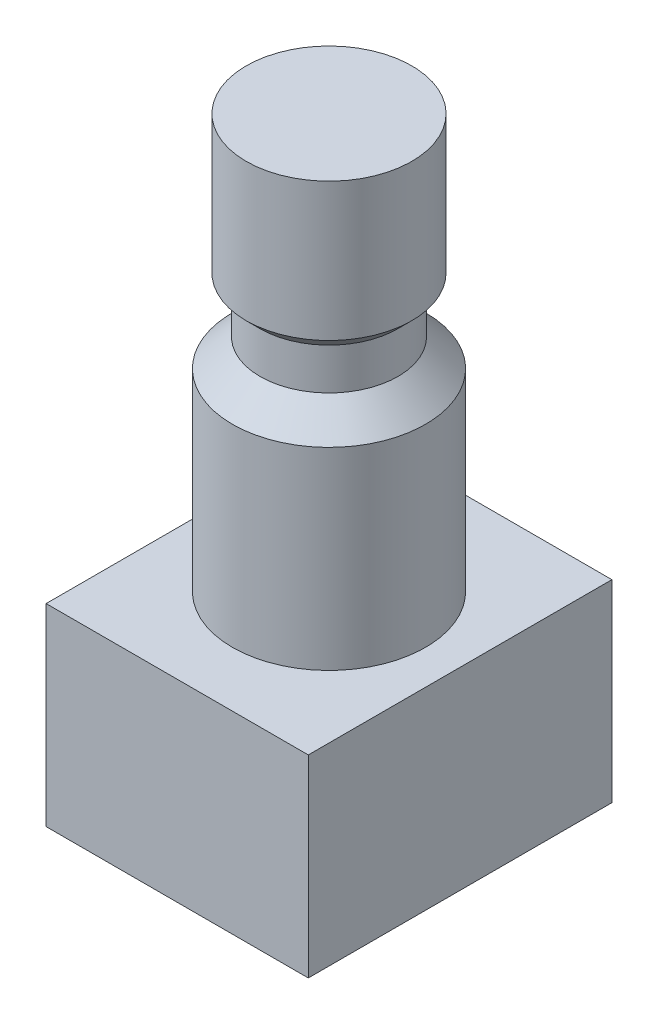
SolidWorks part; units mm, degrees
ref_plane "Plan de face" through (0, 0, 0) normal (0, 0, 1) x (1, 0, 0)
ref_plane "Plan de dessus" through (0, 0, 0) normal (0, 1, 0) x (1, 0, 0)
ref_plane "Plan de droite" through (0, 0, 0) normal (1, 0, 0) x (0, 0, -1)
sketch "Esquisse1" plane through (0, 0, 0) normal (0, 1, 0) x (1, 0, 0)
  line L0 (-4.75, 5.5) -> (4.75, -5.5) construction
  line L1 (-4.75, -5.5) -> (4.75, -5.5)
  line L2 (-4.75, -5.5) -> (-4.75, 5.5)
  line L3 (-4.75, 5.5) -> (4.75, 5.5)
  line L4 (4.75, -5.5) -> (4.75, 5.5)
  point P5 (0, 0)
  dimension "D1" = 11
  dimension "D2" = 9.5
extrude "Boss.-Extru.1" add sketch "Esquisse1" against normal blind 7
sketch "Esquisse3" plane through (0, 0, 0) normal (0, 0, 1) x (1, 0, 0)
  line L0 (0, 0) -> (0, 15)
  line L1 (0, 15) -> (3, 15)
  line L2 (3, 15) -> (3, 10)
  line L3 (3, 10) -> (2.5, 9.5)
  line L4 (2.5, 9.5) -> (2.5, 8)
  line L5 (2.5, 8) -> (3.5, 7)
  line L6 (3.5, 7) -> (3.5, 0)
  line L7 (3.5, 0) -> (0, 0)
  line L8 (0, 0) -> (0, -1.1593) construction
  point P3 (2.5, 5.04)
  point P10 (3, 8.8064)
  point P12 (2.5, 9.6408)
  point P13 (2.5, 7.7311)
  point P14 (2.5, 7.678)
  point P15 (2.5, 9.0403)
  point P16 (2.5, 8)
  dimension "D1" = 7
  dimension "D2" = 5
  dimension "D3" = 6
  dimension "D4" = 7
  dimension "D5" = 15
  dimension "D6" = 135
  dimension "D7" = 5
revolve "Révolution1" add sketch "Esquisse3" angle 360 about L8
